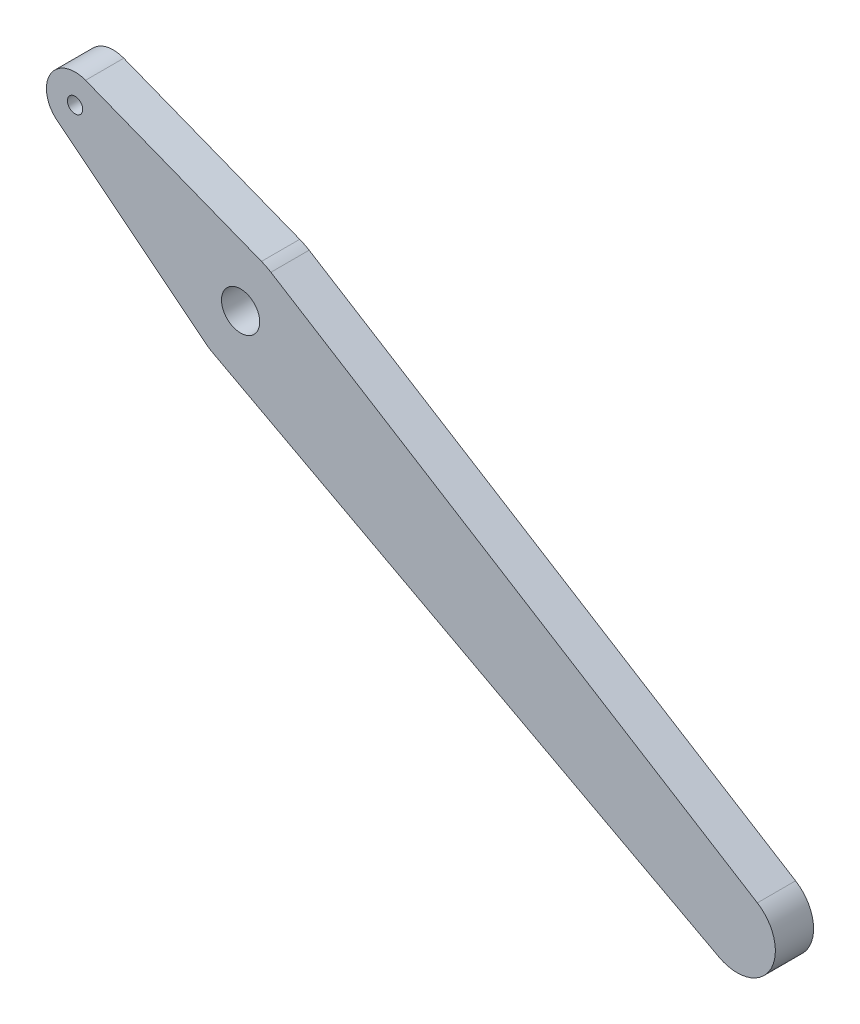
SolidWorks part; units mm, degrees
ref_plane "Front Plane" through (0, 0, 0) normal (0, 0, 1) x (1, 0, 0)
ref_plane "Top Plane" through (0, 0, 0) normal (0, 1, 0) x (1, 0, 0)
ref_plane "Right Plane" through (0, 0, 0) normal (1, 0, 0) x (0, 0, -1)
sketch "Sketch1" plane through (0, 0, 0) normal (0, 0, 1) x (1, 0, 0)
  line L0 (0, 0) -> (129.9038, -75) construction
  line L1 (-43.3013, 25) -> (0, 0) construction
  line L2 (-47.9831, 19.1408) -> (-9.3637, -11.7184)
  line L3 (-40.568, 31.9842) -> (5.4666, 13.9684)
  line L4 (7.9288, 12.7332) -> (135.1897, -66.5112)
  line L5 (-7.0628, -13.2332) -> (125.1953, -83.8221)
  line L6 (0, 0) -> (-15, 0) construction
  circle A0 centre (129.9038, -75) radius 10
  circle A1 centre (0, 0) radius 15
  circle A2 centre (-43.3013, 25) radius 7.5
  point P15 (0, 0)
  dimension "D1" = 20
  dimension "D2" = 30
  dimension "D4" = 15
  dimension "D3" = 150
  dimension "D5" = 50
  dimension "D6" = 30
extrude "Boss-Extrude1" add sketch "Sketch1" along normal mid plane 10 contours A2 | A2 L2 A1 L3 | A1 | A1 L5 A0 L4 | A0 L2
sketch "Sketch2" plane through (0, 0, 0) normal (0, 0, 1) x (1, 0, 0)
  circle A0 centre (-43.3013, 25) radius 2
  circle A1 centre (0, 0) radius 5
  dimension "D1" = 4
  dimension "D2" = 10
extrude "Cut-Extrude1" cut sketch "Sketch2" against normal through all both and the other way through all
